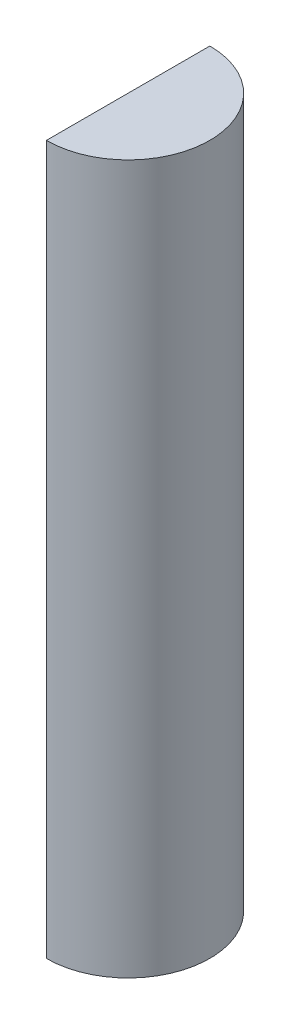
SolidWorks part; units mm, degrees
ref_plane "Front Plane" through (0, 0, 0) normal (0, 0, 1) x (1, 0, 0)
ref_plane "Top Plane" through (0, 0, 0) normal (0, 1, 0) x (1, 0, 0)
ref_plane "Right Plane" through (0, 0, 0) normal (1, 0, 0) x (0, 0, -1)
sketch "Sketch1" plane through (0, 0, 0) normal (0, 1, 0) x (1, 0, 0)
  line L0 (-6.35, 4.7625) -> (9.398, 4.7621)
  circle A0 centre (-6.35, 0) radius 2.3813
  circle A1 centre (9.4615, 0) radius 2.3813
  circle A2 centre (-6.35, 0) radius 4.7625
  circle A3 centre (9.4615, 0) radius 4.7625
  circle A4 centre (1.524, -6.35) radius 2.3812
  circle A5 centre (1.524, -6.35) radius 5.353
  arc A6 (-8.1764, -4.3984) -> (-3.1815, -8.9019) centre (-12.0416, -13.707) cw
  arc A7 (6.5046, -8.3115) -> (10.6745, -4.6054) centre (12.2461, -10.5726) cw
  dimension "D1" = 4.7625
  dimension "D2" = 6.35
  dimension "D3" = 0
  dimension "D5" = 4.7625
  dimension "D6" = 9.525
  dimension "D7" = 9.525
  dimension "D8" = 4.7625
  dimension "D9" = 7.874
  dimension "D10" = 6.35
  dimension "D4" = 15.8115
extrude "Boss-Extrude1" add sketch "Sketch1" along normal blind 1.5875 contours A2 A0 | A2 A6 A5 | A5 A3 L0 A2 | A3 A1 | A5 A7 A3 | A5 A4
sketch "Sketch2" plane through (0, 0, 0) normal (0, -1, 0) x (1, 0, 0)
  circle A0 centre (1.524, 6.35) radius 3.175
  dimension "D1" = 6.35
extrude "Boss-Extrude2" add sketch "Sketch2" along normal blind 1.5875
sketch "Sketch3" plane through (0, 0, 0) normal (0, 1, 0) x (1, 0, 0)
  circle A0 centre (1.524, -6.35) radius 2.3812
extrude "Boss-Extrude3" add sketch "Sketch3" along normal blind 19.05
sketch "Sketch4" plane through (0, 19.05, 0) normal (0, 1, 0) x (1, 0, 0)
  circle A0 centre (1.524, -6.35) radius 3.175
  dimension "D1" = 6.35
extrude "Boss-Extrude4" add sketch "Sketch4" against normal blind 1.5875
sketch "Sketch5" plane through (0, 17.4625, 0) normal (0, -1, 0) x (1, 0, 0)
  line L0 (-6.35, -4.7625) -> (9.4615, -4.7625)
  circle A0 centre (-6.35, 0) radius 2.3813
  circle A1 centre (9.4615, 0) radius 2.3813
  circle A2 centre (1.524, 6.35) radius 5.353
  circle A3 centre (-6.35, 0) radius 4.7625
  circle A4 centre (9.4615, 0) radius 4.7625
  arc A5 (-8.1764, 4.3984) -> (-3.1815, 8.9019) centre (-12.0416, 13.707) ccw
  arc A6 (6.5046, 8.3115) -> (10.6745, 4.6054) centre (12.2461, 10.5726) ccw
  circle M1 centre (1.524, 6.35) radius 2.3812
  circle M2 centre (1.524, 6.35) radius 3.175
extrude "Boss-Extrude5" add sketch "Sketch5" along normal blind 1.5875 separate body contours A2 M2 | A6 A2 A4 | A4 A1 | A5 A3 A2 | A4 A2 A3 L0 | A3 A0 | M2 M1
sketch "Sketch9" plane through (0, -1.5875, 0) normal (0, -1, 0) x (1, 0, 0)
  line L1 (-12.751, 13.2315) -> (15.107, 13.2315)
  line L2 (-12.751, 13.2315) -> (-12.751, -5.7548)
  line L3 (-12.751, -5.7548) -> (15.107, -5.7548)
  line L4 (15.107, 13.2315) -> (15.107, -5.7548)
  circle A0 centre (1.524, 6.35) radius 2.3813
  dimension "D1" = 4.7625
extrude "Cut-Extrude4" cut sketch "Sketch9" against normal through all
sketch "Sketch12" plane through (0, -1.5875, 0) normal (0, -1, 0) x (1, 0, 0)
  line L1 (1.524, 8.7312) -> (-1.4522, 8.7312)
  line L2 (1.524, 8.7312) -> (1.524, 3.7799)
  line L3 (1.524, 3.7799) -> (-1.4522, 3.7799)
  line L4 (-1.4522, 8.7312) -> (-1.4522, 3.7799)
  circle A0 centre (1.524, 6.35) radius 2.3812 construction
extrude "Cut-Extrude5" cut sketch "Sketch12" against normal through all
